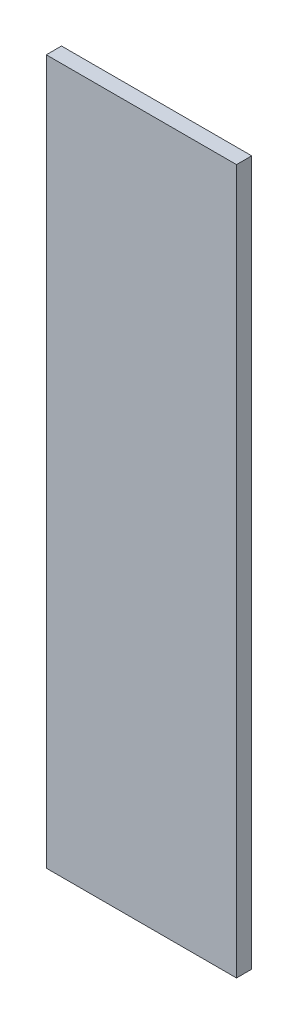
SolidWorks part; units mm, degrees
ref_plane "Front Plane" through (0, 0, 0) normal (0, 0, 1) x (1, 0, 0)
ref_plane "Top Plane" through (0, 0, 0) normal (0, 1, 0) x (1, 0, 0)
ref_plane "Right Plane" through (0, 0, 0) normal (1, 0, 0) x (0, 0, -1)
sketch "Sketch1" plane through (0, 0, 0) normal (0, 0, 1) x (1, 0, 0)
  line L1 (-12.5, -46.29) -> (12.5, -46.29)
  line L2 (-12.5, -46.29) -> (-12.5, 46.29)
  line L3 (-12.5, 46.29) -> (12.5, 46.29)
  line L4 (12.5, -46.29) -> (12.5, 46.29)
  line L5 (-12.5, -46.29) -> (12.5, 46.29) construction
  line L6 (-12.5, 46.29) -> (12.5, -46.29) construction
  point P0 (0, 0)
  dimension "D1" = 25
  dimension "D2" = 92.58
extrude "Boss-Extrude1" add sketch "Sketch1" along normal blind 2
